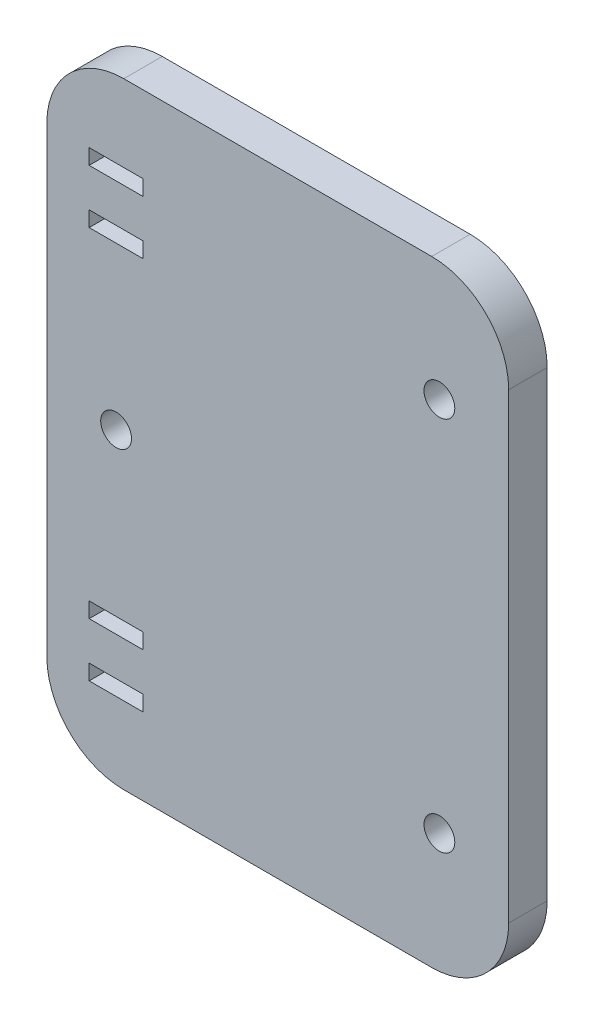
SolidWorks part; units mm, degrees
ref_plane "Front Plane" through (0, 0, 0) normal (0, 0, 1) x (1, 0, 0)
ref_plane "Top Plane" through (0, 0, 0) normal (0, 1, 0) x (1, 0, 0)
ref_plane "Right Plane" through (0, 0, 0) normal (1, 0, 0) x (0, 0, -1)
sketch "Sketch1" plane through (0, 0, 0) normal (0, 0, 1) x (1, 0, 0)
  line L0 (0, 0) -> (0, 80)
  line L3 (-40, 76.0317) -> (-40, -1.9659) construction
  line L4 (-20, 76.0317) -> (-20, -1.9659) construction
  line L5 (-7, 78.5532) -> (-7, -26.8444) construction
  line L6 (0, 0) -> (-34.641, 60) construction
  line L7 (0, 80) -> (-34.641, 20) construction
  line L8 (-60, 40) -> (0, 40) construction
  line L9 (0, 80) -> (-60, 80)
  line L10 (-60, 80) -> (-60, 0)
  line L11 (-60, 0) -> (0, 0)
  dimension "D1" = 80
  dimension "D2" = 20
  dimension "D3" = 20
  dimension "D4" = 7
  dimension "D5" = 60
extrude "Boss-Extrude1" add sketch "Sketch1" along normal blind 5
sketch "Sketch2" plane through (0, 0, 5) normal (0, 0, 1) x (1, 0, 0)
  line L1 (0, 80) -> (-34.641, 20) construction
  line L7 (-20, 76.0317) -> (-20, -1.9659) construction
  line L8 (0, 0) -> (-34.641, 60) construction
  line L10 (-40, 76.0317) -> (-40, -1.9659) construction
  circle A0 centre (-9, 64.4115) radius 12 construction
  circle A1 centre (-9, 15.5885) radius 12 construction
  circle A2 centre (-51, 40) radius 12 construction
  circle A3 centre (-51, 40) radius 2
  circle A4 centre (-9, 64.4115) radius 2
  circle A5 centre (-9, 15.5885) radius 2
  dimension "D1" = 11
  dimension "D2" = 11
  dimension "D3" = 11
extrude "Cut-Extrude1" cut sketch "Sketch2" against normal blind 5
sketch "Sketch3" plane through (0, 0, 5) normal (0, 0, 1) x (1, 0, 0)
  line L0 (-51, 83.4682) -> (-51, -9.3581) construction
  line L1 (-54.5, 70) -> (-47.5, 70)
  line L2 (-54.5, 63) -> (-47.5, 63)
  line L3 (-54.5, 63) -> (-54.5, 61)
  line L4 (-54.5, 61) -> (-47.5, 61)
  line L5 (-47.5, 63) -> (-47.5, 61)
  line L6 (-54.5, 68) -> (-47.5, 68)
  line L7 (-54.5, 70) -> (-54.5, 68)
  line L8 (-47.5, 70) -> (-47.5, 68)
  line L9 (0, 80) -> (-60, 80) construction
  line L10 (-60, 40) -> (-32.9855, 40) construction
  line L11 (-60, 80) -> (-60, 0) construction
  line L12 (-60, 40) -> (0, 40) construction
  line L13 (-54.5, 17) -> (-54.5, 19)
  line L14 (-54.5, 19) -> (-47.5, 19)
  line L15 (-47.5, 17) -> (-47.5, 19)
  line L16 (-54.5, 17) -> (-47.5, 17)
  line L17 (-54.5, 10) -> (-54.5, 12)
  line L18 (-47.5, 10) -> (-47.5, 12)
  line L19 (-54.5, 12) -> (-47.5, 12)
  line L20 (-54.5, 10) -> (-47.5, 10)
  point P7 (-51, 63)
  point P12 (-51, 69.2704)
  dimension "D1" = 7
  dimension "D2" = 2
  dimension "D3" = 2
  dimension "D4" = 5
  dimension "D5" = 10
extrude "Cut-Extrude2" cut sketch "Sketch3" against normal blind 5
fillet "Fillet2" radius 10 4 edges at (-60, 0, 2.5) (0, 0, 2.5) (0, 80, 2.5) (-60, 80, 2.5)
